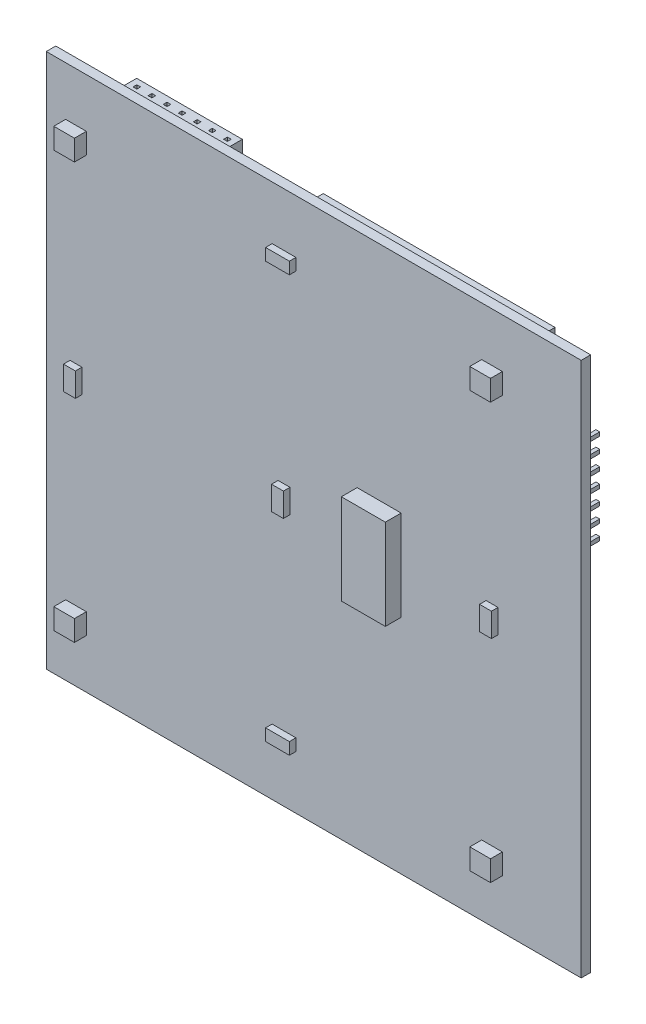
SolidWorks part; units mm, degrees
ref_plane "正面" through (0, 0, 0) normal (0, 0, 1) x (1, 0, 0)
ref_plane "平面" through (0, 0, 0) normal (0, 1, 0) x (1, 0, 0)
ref_plane "右側面" through (0, 0, 0) normal (1, 0, 0) x (0, 0, -1)
sketch "ｽｹｯﾁ1" plane through (0, 0, 0) normal (0, 0, 1) x (1, 0, 0)
  line L0 (-45, 0) -> (45, 0) construction
  line L1 (-45, 45) -> (45, 45)
  line L2 (-45, 45) -> (-45, -45)
  line L3 (-45, -45) -> (45, -45)
  line L4 (45, 45) -> (45, -45)
  line L5 (0, -45) -> (0, 45) construction
  point P8 (0, 0)
  dimension "D1" = 90
  dimension "D2" = 90
  dimension "D3" = 0
  dimension "D4" = 0
extrude "ﾎﾞｽ - 押し出し1" add sketch "ｽｹｯﾁ1" along normal blind 1.6
sketch "ｽｹｯﾁ4" plane through (0, 0, 0) normal (0, 0, -1) x (-1, 0, 0)
  line L0 (-45, -45) -> (-45, 45) construction
  line L1 (-23.89, -36.1) -> (-6.11, -36.1)
  line L2 (-23.89, -36.1) -> (-23.89, -44.6)
  line L3 (-23.89, -44.6) -> (-6.11, -44.6)
  line L4 (-6.11, -36.1) -> (-6.11, -44.6)
  line L6 (45, 45) -> (45, -45) construction
  line L8 (-38.85, 26.89) -> (-36.35, 26.89)
  line L9 (-38.85, 26.89) -> (-38.85, 9.11)
  line L10 (-38.85, 9.11) -> (-36.35, 9.11)
  line L11 (-36.35, 26.89) -> (-36.35, 9.11)
  line L12 (16.11, 44.6) -> (33.89, 44.6)
  line L13 (16.11, 44.6) -> (16.11, 36.1)
  line L14 (16.11, 36.1) -> (33.89, 36.1)
  line L15 (33.89, 44.6) -> (33.89, 36.1)
  line L16 (-45, 45) -> (45, 45) construction
  line L17 (45, -45) -> (-45, -45) construction
  line L18 (36.1, 26.89) -> (44.6, 26.89)
  line L19 (36.1, 26.89) -> (36.1, 9.11)
  line L20 (36.1, 9.11) -> (44.6, 9.11)
  line L21 (44.6, 26.89) -> (44.6, 9.11)
  point P6 (25, 44.6)
  point P7 (-15, -44.6)
  point P14 (-38.85, 18)
  point P15 (-37.6, 9.11)
  point P25 (44.6, 18)
  dimension "D2" = 8.5
  dimension "D3" = 8.5
  dimension "D4" = 17.78
  dimension "D5" = 2.5
  dimension "D6" = 17.78
  dimension "D7" = 27
  dimension "D8" = 7.4
  dimension "D9" = 20
  dimension "D10" = 30
  dimension "D11" = 0.4
  dimension "D12" = 17.78
  dimension "D13" = 17.78
  dimension "D14" = 0.4
  dimension "D15" = 27
  dimension "D16" = 8.5
  dimension "D17" = 0.4
extrude "ﾎﾞｽ - 押し出し2" add sketch "ｽｹｯﾁ4" along normal blind 2.5
sketch "ｽｹｯﾁ5" plane through (0, 0, -2.5) normal (0, 0, -1) x (-1, 0, 0)
  line L8 (-38.85, 9.11) -> (-36.35, 9.11) construction
  line L33 (-37.92, 18.32) -> (-37.28, 18.32)
  line L34 (-37.92, 18.32) -> (-37.92, 17.68)
  line L35 (-37.92, 17.68) -> (-37.28, 17.68)
  line L36 (-37.28, 18.32) -> (-37.28, 17.68)
  line L37 (-38.85, 26.89) -> (-38.85, 9.11) construction
  line L39 (-37.92, 15.78) -> (-37.28, 15.78)
  line L40 (-37.92, 15.78) -> (-37.92, 15.14)
  line L41 (-37.92, 15.14) -> (-37.28, 15.14)
  line L42 (-37.28, 15.78) -> (-37.28, 15.14)
  line L45 (-37.92, 13.24) -> (-37.28, 13.24)
  line L46 (-37.92, 13.24) -> (-37.92, 12.6)
  line L47 (-37.92, 12.6) -> (-37.28, 12.6)
  line L48 (-37.28, 13.24) -> (-37.28, 12.6)
  line L49 (-37.92, 10.7) -> (-37.28, 10.7)
  line L50 (-37.92, 10.7) -> (-37.92, 10.06)
  line L51 (-37.92, 10.06) -> (-37.28, 10.06)
  line L52 (-37.28, 10.7) -> (-37.28, 10.06)
  line L53 (-37.92, 20.86) -> (-37.28, 20.86)
  line L54 (-37.92, 20.86) -> (-37.92, 20.22)
  line L55 (-37.92, 20.22) -> (-37.28, 20.22)
  line L56 (-37.28, 20.86) -> (-37.28, 20.22)
  line L57 (-37.92, 23.4) -> (-37.28, 23.4)
  line L58 (-37.92, 23.4) -> (-37.92, 22.76)
  line L59 (-37.92, 22.76) -> (-37.28, 22.76)
  line L60 (-37.28, 23.4) -> (-37.28, 22.76)
  line L61 (-37.92, 25.94) -> (-37.28, 25.94)
  line L62 (-37.92, 25.94) -> (-37.92, 25.3)
  line L63 (-37.92, 25.3) -> (-37.28, 25.3)
  line L64 (-37.28, 25.94) -> (-37.28, 25.3)
  point P47 (-37.6, 17.68)
  point P50 (-37.6, 9.11)
  point P53 (-37.92, 18)
  point P54 (-38.85, 18)
  point P59 (-37.28, 15.46)
  point P60 (-37.28, 18)
  point P61 (-37.28, 12.92)
  point P70 (-37.28, 10.38)
  point P83 (-37.28, 20.54)
  point P84 (-37.28, 23.08)
  point P85 (-37.28, 25.62)
  point P179 (-37.6, 10.7)
  point P180 (-37.6, 13.24)
  point P181 (-37.6, 15.78)
  point P182 (-37.6, 18.32)
  point P183 (-37.6, 20.86)
  point P184 (-37.6, 23.4)
  point P185 (-37.6, 25.94)
  dimension "D21" = 0.64
  dimension "D22" = 0.64
  dimension "D23" = 0.64
  dimension "D24" = 0.64
  dimension "D25" = 2.54
  dimension "D26" = 0.64
  dimension "D27" = 2.54
  dimension "D28" = 0.64
  dimension "D29" = 2.54
  dimension "D30" = 0.64
  dimension "D31" = 0.64
  dimension "D32" = 0.64
  dimension "D33" = 0.64
  dimension "D34" = 2.54
  dimension "D35" = 2.54
  dimension "D36" = 0.64
  dimension "D37" = 0.64
  dimension "D38" = 0.64
  dimension "D39" = 2.54
  dimension "D40" = 0.64
extrude "ﾎﾞｽ - 押し出し3" add sketch "ｽｹｯﾁ5" along normal blind 6.1
sketch "ｽｹｯﾁ6" plane through (0, 0, 1.6) normal (0, 0, 1) x (1, 0, 0)
  line L0 (-45, -45) -> (45, -45) construction
  line L1 (-41.74, -33.26) -> (-38.26, -33.26)
  line L2 (-41.74, -33.26) -> (-41.74, -36.74)
  line L3 (-41.74, -36.74) -> (-38.26, -36.74)
  line L4 (-38.26, -33.26) -> (-38.26, -36.74)
  line L5 (-45, 45) -> (-45, -45) construction
  line L6 (45, 45) -> (-45, 45) construction
  line L7 (-41.74, 36.74) -> (-38.26, 36.74)
  line L8 (-41.74, 36.74) -> (-41.74, 33.26)
  line L9 (-41.74, 33.26) -> (-38.26, 33.26)
  line L10 (-38.26, 36.74) -> (-38.26, 33.26)
  line L11 (45, -45) -> (45, 45) construction
  line L12 (28.26, -33.26) -> (31.74, -33.26)
  line L13 (28.26, -33.26) -> (28.26, -36.74)
  line L14 (28.26, -36.74) -> (31.74, -36.74)
  line L15 (31.74, -33.26) -> (31.74, -36.74)
  line L17 (28.26, 36.74) -> (31.74, 36.74)
  line L18 (28.26, 36.74) -> (28.26, 33.26)
  line L19 (28.26, 33.26) -> (31.74, 33.26)
  line L20 (31.74, 36.74) -> (31.74, 33.26)
  point P4 (-41.74, -35)
  point P7 (-40, -36.74)
  point P14 (-41.74, 35)
  point P17 (-40, 36.74)
  point P22 (30, -36.74)
  point P25 (31.74, -35)
  point P30 (30, 36.74)
  point P31 (31.74, 35)
  dimension "D1" = 3.48
  dimension "D2" = 3.48
  dimension "D3" = 10
  dimension "D4" = 5
  dimension "D5" = 3.48
  dimension "D6" = 3.48
  dimension "D7" = 10
  dimension "D8" = 5
  dimension "D9" = 15
  dimension "D10" = 10
  dimension "D11" = 3.48
  dimension "D12" = 3.48
  dimension "D13" = 15
  dimension "D14" = 10
  dimension "D15" = 3.48
  dimension "D16" = 3.48
extrude "ﾎﾞｽ - 押し出し4" add sketch "ｽｹｯﾁ6" along normal blind 2
sketch "ｽｹｯﾁ7" plane through (0, 0, 1.6) normal (0, 0, 1) x (1, 0, 0)
  line L0 (-45, -45) -> (45, -45) construction
  line L1 (-41, 2) -> (-39, 2)
  line L2 (-41, 2) -> (-41, -2)
  line L3 (-41, -2) -> (-39, -2)
  line L4 (-39, 2) -> (-39, -2)
  line L5 (-45, 45) -> (-45, -45) construction
  line L6 (45, -45) -> (45, 45) construction
  line L7 (29, 2) -> (31, 2)
  line L8 (29, 2) -> (29, -2)
  line L9 (29, -2) -> (31, -2)
  line L10 (31, 2) -> (31, -2)
  line L11 (45, 45) -> (-45, 45) construction
  line L12 (-7, 36) -> (-3, 36)
  line L13 (-7, 36) -> (-7, 34)
  line L14 (-7, 34) -> (-3, 34)
  line L15 (-3, 36) -> (-3, 34)
  line L17 (-7, -34) -> (-3, -34)
  line L18 (-7, -34) -> (-7, -36)
  line L19 (-7, -36) -> (-3, -36)
  line L20 (-3, -34) -> (-3, -36)
  line L21 (-6, 2) -> (-4, 2)
  line L22 (-6, 2) -> (-6, -2)
  line L23 (-6, -2) -> (-4, -2)
  line L24 (-4, 2) -> (-4, -2)
  point P4 (-41, 0)
  point P7 (-40, -2)
  point P14 (30, 2)
  point P17 (31, 0)
  point P22 (-7, 35)
  point P25 (-5, 36)
  point P30 (-7, -35)
  point P31 (-5, -36)
  point P36 (-4, 0)
  point P37 (29, 0)
  point P38 (-5, 34)
  point P39 (-5, 2)
  dimension "D1" = 4
  dimension "D2" = 2
  dimension "D3" = 45
  dimension "D4" = 5
  dimension "D5" = 4
  dimension "D6" = 2
  dimension "D7" = 15
  dimension "D8" = 45
  dimension "D9" = 4
  dimension "D10" = 2
  dimension "D11" = 10
  dimension "D12" = 40
  dimension "D13" = 4
  dimension "D14" = 2
  dimension "D15" = 10
  dimension "D16" = 40
  dimension "D17" = 4
  dimension "D18" = 2
extrude "ﾎﾞｽ - 押し出し5" add sketch "ｽｹｯﾁ7" along normal blind 1.1
sketch "ｽｹｯﾁ8" plane through (0, 0, 1.6) normal (0, 0, 1) x (1, 0, 0)
  line L1 (7.3, 7.6) -> (14.7, 7.6)
  line L2 (7.3, 7.6) -> (7.3, -7.6)
  line L3 (7.3, -7.6) -> (14.7, -7.6)
  line L4 (14.7, 7.6) -> (14.7, -7.6)
  line L5 (-45, 45) -> (-45, -45) construction
  point P4 (7.3, 0)
  point P11 (-45, 0)
  point P12 (11, 7.6)
  dimension "D1" = 15.2
  dimension "D2" = 7.4
  dimension "D3" = 56
extrude "ﾎﾞｽ - 押し出し6" add sketch "ｽｹｯﾁ8" along normal blind 2.65
sketch "ｽｹｯﾁ9" plane through (0, -44.6, 0) normal (0, -1, 0) x (1, 0, 0)
  line L1 (14.68, -0.93) -> (15.32, -0.93)
  line L2 (14.68, -0.93) -> (14.68, -1.57)
  line L3 (14.68, -1.57) -> (15.32, -1.57)
  line L4 (15.32, -0.93) -> (15.32, -1.57)
  line L5 (6.11, -2.5) -> (6.11, 0) construction
  line L6 (6.11, -1.25) -> (23.89, -1.25) construction
  line L7 (23.89, -2.5) -> (23.89, 0) construction
  line L8 (23.89, -2.5) -> (6.11, -2.5) construction
  line L10 (15, -2.5) -> (15, 0) construction
  line L11 (23.89, 0) -> (6.11, 0) construction
  line L13 (12.14, -0.93) -> (12.78, -0.93)
  line L14 (12.14, -0.93) -> (12.14, -1.57)
  line L15 (12.14, -1.57) -> (12.78, -1.57)
  line L16 (12.78, -0.93) -> (12.78, -1.57)
  line L17 (9.6, -0.93) -> (10.24, -0.93)
  line L18 (9.6, -0.93) -> (9.6, -1.57)
  line L19 (9.6, -1.57) -> (10.24, -1.57)
  line L20 (10.24, -0.93) -> (10.24, -1.57)
  line L21 (7.06, -0.93) -> (7.7, -0.93)
  line L22 (7.06, -0.93) -> (7.06, -1.57)
  line L23 (7.06, -1.57) -> (7.7, -1.57)
  line L24 (7.7, -0.93) -> (7.7, -1.57)
  line L25 (17.22, -0.93) -> (17.86, -0.93)
  line L26 (17.22, -0.93) -> (17.22, -1.57)
  line L27 (17.22, -1.57) -> (17.86, -1.57)
  line L28 (17.86, -0.93) -> (17.86, -1.57)
  line L29 (19.76, -0.93) -> (20.4, -0.93)
  line L30 (19.76, -0.93) -> (19.76, -1.57)
  line L31 (19.76, -1.57) -> (20.4, -1.57)
  line L32 (20.4, -0.93) -> (20.4, -1.57)
  line L33 (22.3, -0.93) -> (22.94, -0.93)
  line L34 (22.3, -0.93) -> (22.3, -1.57)
  line L35 (22.3, -1.57) -> (22.94, -1.57)
  line L36 (22.94, -0.93) -> (22.94, -1.57)
  point P10 (15.32, -1.25)
  point P13 (15, -1.57)
  point P42 (12.46, -1.57)
  point P43 (9.92, -1.57)
  point P44 (12.14, -1.25)
  point P46 (9.6, -1.25)
  point P47 (7.06, -1.25)
  point P48 (7.38, -1.57)
  point P49 (17.54, -1.57)
  point P50 (20.08, -1.57)
  point P51 (22.62, -1.57)
  point P52 (17.22, -1.25)
  point P53 (19.76, -1.25)
  point P54 (22.3, -1.25)
  dimension "D1" = 0.64
  dimension "D2" = 0.64
  dimension "D3" = 0.64
  dimension "D4" = 0.64
  dimension "D5" = 0.64
  dimension "D6" = 0.64
  dimension "D7" = 0.64
  dimension "D8" = 0.64
  dimension "D9" = 0.64
  dimension "D10" = 0.64
  dimension "D11" = 0.64
  dimension "D12" = 2.54
  dimension "D13" = 2.54
  dimension "D14" = 2.54
  dimension "D15" = 0.64
  dimension "D16" = 0.64
  dimension "D17" = 0.64
  dimension "D18" = 2.54
  dimension "D19" = 2.54
  dimension "D20" = 2.54
extrude "ｶｯﾄ - 押し出し1" cut sketch "ｽｹｯﾁ9" against normal blind 7.5
sketch "ｽｹｯﾁ10" plane through (-44.6, 0, 0) normal (-1, 0, 0) x (0, 0, 1)
  line L0 (-1.25, 26.89) -> (-1.25, 9.11) construction
  line L1 (-2.5, 26.89) -> (0, 26.89) construction
  line L2 (-2.5, 9.11) -> (0, 9.11) construction
  line L3 (-2.5, 18) -> (0, 18) construction
  line L4 (-2.5, 9.11) -> (-2.5, 26.89) construction
  line L5 (0, 9.11) -> (0, 26.89) construction
  line L7 (-1.57, 18.32) -> (-0.93, 18.32)
  line L8 (-1.57, 18.32) -> (-1.57, 17.68)
  line L9 (-1.57, 17.68) -> (-0.93, 17.68)
  line L10 (-0.93, 18.32) -> (-0.93, 17.68)
  line L11 (-1.57, 25.94) -> (-0.93, 25.94)
  line L12 (-1.57, 25.94) -> (-1.57, 25.3)
  line L13 (-1.57, 25.3) -> (-0.93, 25.3)
  line L14 (-0.93, 25.94) -> (-0.93, 25.3)
  line L15 (-1.57, 23.4) -> (-0.93, 23.4)
  line L16 (-1.57, 23.4) -> (-1.57, 22.76)
  line L17 (-1.57, 22.76) -> (-0.93, 22.76)
  line L18 (-0.93, 23.4) -> (-0.93, 22.76)
  line L19 (-1.57, 20.86) -> (-0.93, 20.86)
  line L20 (-1.57, 20.86) -> (-1.57, 20.22)
  line L21 (-1.57, 20.22) -> (-0.93, 20.22)
  line L22 (-0.93, 20.86) -> (-0.93, 20.22)
  line L23 (-1.57, 15.78) -> (-0.93, 15.78)
  line L24 (-1.57, 15.78) -> (-1.57, 15.14)
  line L25 (-1.57, 15.14) -> (-0.93, 15.14)
  line L26 (-0.93, 15.78) -> (-0.93, 15.14)
  line L27 (-1.57, 13.24) -> (-0.93, 13.24)
  line L28 (-1.57, 13.24) -> (-1.57, 12.6)
  line L29 (-1.57, 12.6) -> (-0.93, 12.6)
  line L30 (-0.93, 13.24) -> (-0.93, 12.6)
  line L31 (-1.57, 10.7) -> (-0.93, 10.7)
  line L32 (-1.57, 10.7) -> (-1.57, 10.06)
  line L33 (-1.57, 10.06) -> (-0.93, 10.06)
  line L34 (-0.93, 10.7) -> (-0.93, 10.06)
  point P16 (-1.25, 18.32)
  point P17 (-1.57, 18)
  point P30 (-1.57, 20.54)
  point P31 (-0.93, 23.08)
  point P32 (-0.93, 20.54)
  point P33 (-0.93, 25.62)
  point P34 (-1.25, 20.86)
  point P35 (-1.25, 23.4)
  point P36 (-1.25, 25.94)
  point P49 (-0.93, 15.46)
  point P50 (-0.93, 12.92)
  point P51 (-0.93, 10.38)
  dimension "D1" = 0.64
  dimension "D2" = 0.64
  dimension "D3" = 0.64
  dimension "D4" = 0.64
  dimension "D5" = 0.64
  dimension "D6" = 2.54
  dimension "D7" = 2.54
  dimension "D8" = 2.54
  dimension "D9" = 0.64
  dimension "D10" = 0.64
  dimension "D11" = 0.64
  dimension "D12" = 0.64
  dimension "D13" = 0.64
  dimension "D14" = 0.64
  dimension "D15" = 2.54
  dimension "D16" = 2.54
  dimension "D17" = 2.54
  dimension "D18" = 0.64
  dimension "D19" = 0.64
  dimension "D20" = 0.64
extrude "ｶｯﾄ - 押し出し2" cut sketch "ｽｹｯﾁ10" against normal blind 7.5
sketch "ｽｹｯﾁ11" plane through (0, 44.6, 0) normal (0, 1, 0) x (1, 0, 0)
  line L0 (-33.89, 1.25) -> (-16.11, 1.25) construction
  line L1 (-33.89, 2.5) -> (-33.89, 0) construction
  line L2 (-16.11, 2.5) -> (-16.11, 0) construction
  line L3 (-25, 2.5) -> (-25, 0) construction
  line L4 (-33.89, 2.5) -> (-16.11, 2.5) construction
  line L5 (45, 0) -> (-45, 0) construction
  line L7 (-25.32, 1.57) -> (-24.68, 1.57)
  line L8 (-25.32, 1.57) -> (-25.32, 0.93)
  line L9 (-25.32, 0.93) -> (-24.68, 0.93)
  line L10 (-24.68, 1.57) -> (-24.68, 0.93)
  line L11 (-32.94, 1.57) -> (-32.3, 1.57)
  line L12 (-32.94, 1.57) -> (-32.94, 0.93)
  line L13 (-32.94, 0.93) -> (-32.3, 0.93)
  line L14 (-32.3, 1.57) -> (-32.3, 0.93)
  line L15 (-30.4, 1.57) -> (-29.76, 1.57)
  line L16 (-30.4, 1.57) -> (-30.4, 0.93)
  line L17 (-30.4, 0.93) -> (-29.76, 0.93)
  line L18 (-29.76, 1.57) -> (-29.76, 0.93)
  line L19 (-27.86, 1.57) -> (-27.22, 1.57)
  line L20 (-27.86, 1.57) -> (-27.86, 0.93)
  line L21 (-27.86, 0.93) -> (-27.22, 0.93)
  line L22 (-27.22, 1.57) -> (-27.22, 0.93)
  line L23 (-22.78, 1.57) -> (-22.14, 1.57)
  line L24 (-22.78, 1.57) -> (-22.78, 0.93)
  line L25 (-22.78, 0.93) -> (-22.14, 0.93)
  line L26 (-22.14, 1.57) -> (-22.14, 0.93)
  line L27 (-20.24, 1.57) -> (-19.6, 1.57)
  line L28 (-20.24, 1.57) -> (-20.24, 0.93)
  line L29 (-20.24, 0.93) -> (-19.6, 0.93)
  line L30 (-19.6, 1.57) -> (-19.6, 0.93)
  line L31 (-17.7, 1.57) -> (-17.06, 1.57)
  line L32 (-17.7, 1.57) -> (-17.7, 0.93)
  line L33 (-17.7, 0.93) -> (-17.06, 0.93)
  line L34 (-17.06, 1.57) -> (-17.06, 0.93)
  point P16 (-25, 0.93)
  point P17 (-24.68, 1.25)
  point P42 (-27.54, 1.57)
  point P43 (-30.08, 1.57)
  point P44 (-32.62, 1.57)
  point P45 (-32.94, 1.25)
  point P46 (-30.4, 1.25)
  point P47 (-27.86, 1.25)
  point P48 (-22.46, 1.57)
  point P49 (-19.92, 1.57)
  point P50 (-17.38, 1.57)
  point P52 (-22.78, 1.25)
  point P53 (-20.24, 1.25)
  point P54 (-17.7, 1.25)
  dimension "D1" = 0.64
  dimension "D2" = 0.64
  dimension "D3" = 0.64
  dimension "D4" = 0.64
  dimension "D5" = 0.64
  dimension "D6" = 2.54
  dimension "D7" = 2.54
  dimension "D8" = 2.54
  dimension "D9" = 0.64
  dimension "D10" = 0.64
  dimension "D11" = 0.64
  dimension "D12" = 0.64
  dimension "D13" = 0.64
  dimension "D14" = 0.64
  dimension "D15" = 0.64
  dimension "D16" = 0.64
  dimension "D17" = 0.64
  dimension "D18" = 2.54
  dimension "D19" = 2.54
  dimension "D20" = 2.54
extrude "ｶｯﾄ - 押し出し3" cut sketch "ｽｹｯﾁ11" against normal blind 7.5
sketch "ｽｹｯﾁ12" plane through (0, 0, 0) normal (0, 0, -1) x (-1, 0, 0)
  line L7 (45, 45) -> (45, -45) construction
  line L8 (-45, 45) -> (45, 45) construction
  line L9 (45, -45) -> (-45, -45) construction
  line L16 (-45, -45) -> (-45, 45) construction
  line L24 (-23, 30) -> (-24, 31.7321)
  line L25 (-24, 31.7321) -> (-26, 31.7321)
  line L26 (-26, 31.7321) -> (-27, 30)
  line L27 (-27, 30) -> (-26, 28.2679)
  line L28 (-26, 28.2679) -> (-24, 28.2679)
  line L29 (-24, 28.2679) -> (-23, 30)
  line L30 (37, 30) -> (36, 31.7321)
  line L31 (36, 31.7321) -> (34, 31.7321)
  line L32 (34, 31.7321) -> (33, 30)
  line L33 (33, 30) -> (34, 28.2679)
  line L34 (34, 28.2679) -> (36, 28.2679)
  line L35 (36, 28.2679) -> (37, 30)
  line L36 (37, -30) -> (36, -28.2679)
  line L37 (36, -28.2679) -> (34, -28.2679)
  line L38 (34, -28.2679) -> (33, -30)
  line L39 (33, -30) -> (34, -31.7321)
  line L40 (34, -31.7321) -> (36, -31.7321)
  line L41 (36, -31.7321) -> (37, -30)
  line L42 (-23, -30) -> (-24, -28.2679)
  line L43 (-24, -28.2679) -> (-26, -28.2679)
  line L44 (-26, -28.2679) -> (-27, -30)
  line L45 (-27, -30) -> (-26, -31.7321)
  line L46 (-26, -31.7321) -> (-24, -31.7321)
  line L47 (-24, -31.7321) -> (-23, -30)
  circle A0 centre (35, 30) radius 2 construction
  circle A1 centre (35, -30) radius 2 construction
  circle A2 centre (-25, -30) radius 2 construction
  circle A3 centre (-25, 30) radius 2 construction
  dimension "D1" = 10
  dimension "D2" = 15
  dimension "D3" = 15
  dimension "D4" = 10
  dimension "D5" = 15
  dimension "D6" = 20
  dimension "D7" = 20
  dimension "D8" = 15
extrude "ﾎﾞｽ - 押し出し7" add sketch "ｽｹｯﾁ12" along normal blind 3
sketch "ｽｹｯﾁ13" plane through (0, 0, -3) normal (0, 0, -1) x (-1, 0, 0)
  line L0 (-34, 41) -> (-34, 0)
  line L1 (-34, 0) -> (-36, 0)
  line L2 (-36, 0) -> (-36, -39)
  line L3 (-36, -39) -> (5, -39)
  line L4 (5, -39) -> (5, -41)
  line L5 (5, -41) -> (44, -41)
  line L6 (44, -41) -> (44, 0)
  line L7 (44, 0) -> (46, 0)
  line L8 (46, 0) -> (46, 39)
  line L9 (46, 39) -> (5, 39)
  line L10 (5, 39) -> (5, 41)
  line L11 (5, 41) -> (-34, 41)
  line L12 (5, -57.6044) -> (5, 50.3983) construction
  line L13 (45, 45) -> (45, -45) construction
  line L14 (-24, 31.7321) -> (-26, 31.7321) construction
  line L15 (-24, -28.2679) -> (-26, -28.2679) construction
  line L16 (36, -28.2679) -> (34, -28.2679) construction
  line L18 (36, 31.7321) -> (34, 31.7321) construction
  circle A0 centre (-25, 30) radius 1
  circle A1 centre (-25, -30) radius 1
  circle A2 centre (35, -30) radius 1
  circle A3 centre (35, 30) radius 1
  point P26 (-25, 31.7321)
  point P30 (-25, -28.2679)
  point P38 (35, -28.2679)
  point P46 (35, 31.7321)
  dimension "D1" = 41
  dimension "D2" = 39
  dimension "D3" = 41
  dimension "D4" = 39
  dimension "D5" = 41
  dimension "D6" = 39
  dimension "D7" = 41
  dimension "D8" = 39
  dimension "D9" = 40
extrude "ﾎﾞｽ - 押し出し8" add sketch "ｽｹｯﾁ13" along normal blind 2 separate body
